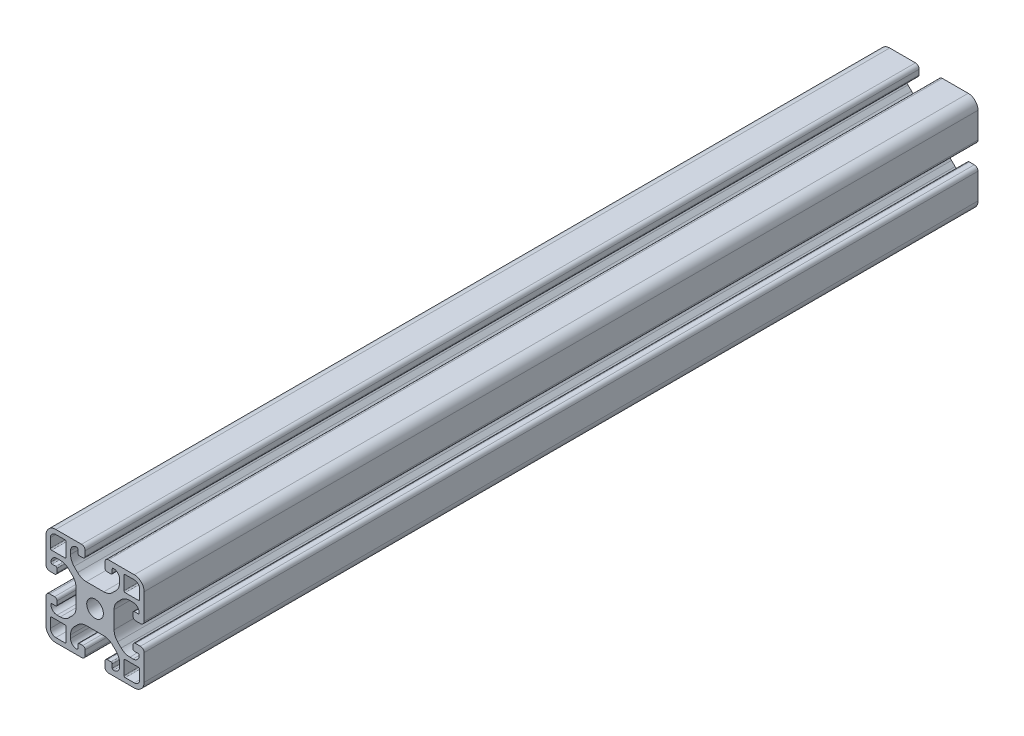
SolidWorks part; units mm, degrees
ref_plane "Plan de face" through (0, 0, 0) normal (0, 0, 1) x (1, 0, 0)
ref_plane "Plan de dessus" through (0, 0, 0) normal (0, 1, 0) x (1, 0, 0)
ref_plane "Plan de droite" through (0, 0, 0) normal (1, 0, 0) x (0, 0, -1)
ref_plane "Plan1" through (0, 0, -30) normal (0, 0, -1) x (-1, 0, 0)
sketch "Esquisse1" plane through (0, 0, -30) normal (0, 0, -1) x (-1, 0, 0)
  line L0 (-4.5, 15) -> (-4.5, 13.5)
  line L1 (-4, 13) -> (-2.5, 13)
  line L2 (-4.5, 10) -> (-5.8076, 10)
  line L3 (-9.3431, 11.4645) -> (-10.7855, 12.9069)
  line L4 (-12.25, 16.4424) -> (-12.25, 23.5576)
  line L5 (-10.7855, 27.0931) -> (-9.3431, 28.5355)
  line L6 (-5.8076, 30) -> (-4.5, 30)
  line L7 (-2.5, 27) -> (-4, 27)
  line L8 (-4.5, 26.5) -> (-4.5, 25)
  line L9 (-3.5, 24) -> (-1.5, 24)
  line L10 (0, 25.5) -> (0, 36)
  line L11 (-4, 40) -> (-14.5, 40)
  line L12 (-16, 38.5) -> (-16, 36.5)
  line L13 (-15, 35.5) -> (-13.5, 35.5)
  line L14 (-13, 36) -> (-13, 37.5)
  line L15 (-10, 35.5) -> (-10, 34.1924)
  line L16 (-11.4645, 30.6569) -> (-12.9069, 29.2145)
  line L17 (-16.4424, 27.75) -> (-23.5576, 27.75)
  line L18 (-27.0931, 29.2145) -> (-28.5355, 30.6569)
  line L19 (-30, 34.1924) -> (-30, 35.5)
  line L20 (-27, 37.5) -> (-27, 36)
  line L21 (-26.5, 35.5) -> (-25, 35.5)
  line L22 (-24, 36.5) -> (-24, 38.5)
  line L23 (-25.5, 40) -> (-36, 40)
  line L24 (-40, 36) -> (-40, 25.5)
  line L25 (-38.5, 24) -> (-36.5, 24)
  line L26 (-35.5, 25) -> (-35.5, 26.5)
  line L27 (-36, 27) -> (-37.5, 27)
  line L28 (-35.5, 30) -> (-34.1924, 30)
  line L29 (-30.6569, 28.5355) -> (-29.2145, 27.0931)
  line L30 (-27.75, 23.5576) -> (-27.75, 16.4424)
  line L31 (-29.2145, 12.9069) -> (-30.6569, 11.4645)
  line L32 (-34.1924, 10) -> (-35.5, 10)
  line L33 (-37.5, 13) -> (-36, 13)
  line L34 (-35.5, 13.5) -> (-35.5, 15)
  line L35 (-36.5, 16) -> (-38.5, 16)
  line L36 (-40, 14.5) -> (-40, 4)
  line L37 (-36, 0) -> (-25.5, 0)
  line L38 (-24, 1.5) -> (-24, 3.5)
  line L39 (-25, 4.5) -> (-26.5, 4.5)
  line L40 (-27, 4) -> (-27, 2.5)
  line L41 (-30, 4.5) -> (-30, 5.8076)
  line L42 (-28.5355, 9.3431) -> (-27.0931, 10.7855)
  line L43 (-23.5576, 12.25) -> (-16.4424, 12.25)
  line L44 (-12.9069, 10.7855) -> (-11.4645, 9.3431)
  line L45 (-10, 5.8076) -> (-10, 4.5)
  line L46 (-13, 2.5) -> (-13, 4)
  line L47 (-13.5, 4.5) -> (-15, 4.5)
  line L48 (-16, 3.5) -> (-16, 1.5)
  line L49 (-14.5, 0) -> (-4, 0)
  line L50 (0, 4) -> (0, 14.5)
  line L51 (-1.5, 16) -> (-3.5, 16)
  line L52 (-4, 1.8) -> (-7.7, 1.8)
  line L53 (-8.2, 2.3) -> (-8.2, 7.7)
  line L54 (-7.7, 8.2) -> (-2.3, 8.2)
  line L55 (-1.8, 7.7) -> (-1.8, 4)
  line L56 (-38.2, 4) -> (-38.2, 7.7)
  line L57 (-37.7, 8.2) -> (-32.3, 8.2)
  line L58 (-31.8, 7.7) -> (-31.8, 2.3)
  line L59 (-32.3, 1.8) -> (-36, 1.8)
  line L60 (-36, 38.2) -> (-32.3, 38.2)
  line L61 (-31.8, 37.7) -> (-31.8, 32.3)
  line L62 (-32.3, 31.8) -> (-37.7, 31.8)
  line L63 (-38.2, 32.3) -> (-38.2, 36)
  line L64 (-1.8, 36) -> (-1.8, 32.3)
  line L65 (-2.3, 31.8) -> (-7.7, 31.8)
  line L66 (-8.2, 32.3) -> (-8.2, 37.7)
  line L67 (-7.7, 38.2) -> (-4, 38.2)
  arc A0 (-4.5, 13.5) -> (-4, 13) centre (-4, 13.5) ccw
  arc A1 (-2.5, 13) -> (-2, 12.5) centre (-2.5, 12.5) cw
  arc A2 (-2, 12.5) -> (-4.5, 10) centre (-4.5, 12.5) cw
  arc A3 (-5.8076, 10) -> (-9.3431, 11.4645) centre (-5.8076, 15) cw
  arc A4 (-10.7855, 12.9069) -> (-12.25, 16.4424) centre (-7.25, 16.4424) cw
  arc A5 (-12.25, 23.5576) -> (-10.7855, 27.0931) centre (-7.25, 23.5576) cw
  arc A6 (-9.3431, 28.5355) -> (-5.8076, 30) centre (-5.8076, 25) cw
  arc A7 (-4.5, 30) -> (-2, 27.5) centre (-4.5, 27.5) cw
  arc A8 (-2, 27.5) -> (-2.5, 27) centre (-2.5, 27.5) cw
  arc A9 (-4, 27) -> (-4.5, 26.5) centre (-4, 26.5) ccw
  arc A10 (-4.5, 25) -> (-3.5, 24) centre (-3.5, 25) ccw
  arc A11 (-1.5, 24) -> (0, 25.5) centre (-1.5, 25.5) ccw
  arc A12 (0, 36) -> (-4, 40) centre (-4, 36) ccw
  arc A13 (-14.5, 40) -> (-16, 38.5) centre (-14.5, 38.5) ccw
  arc A14 (-16, 36.5) -> (-15, 35.5) centre (-15, 36.5) ccw
  arc A15 (-13.5, 35.5) -> (-13, 36) centre (-13.5, 36) ccw
  arc A16 (-13, 37.5) -> (-12.5, 38) centre (-12.5, 37.5) cw
  arc A17 (-12.5, 38) -> (-10, 35.5) centre (-12.5, 35.5) cw
  arc A18 (-10, 34.1924) -> (-11.4645, 30.6569) centre (-15, 34.1924) cw
  arc A19 (-12.9069, 29.2145) -> (-16.4424, 27.75) centre (-16.4424, 32.75) cw
  arc A20 (-23.5576, 27.75) -> (-27.0931, 29.2145) centre (-23.5576, 32.75) cw
  arc A21 (-28.5355, 30.6569) -> (-30, 34.1924) centre (-25, 34.1924) cw
  arc A22 (-30, 35.5) -> (-27.5, 38) centre (-27.5, 35.5) cw
  arc A23 (-27.5, 38) -> (-27, 37.5) centre (-27.5, 37.5) cw
  arc A24 (-27, 36) -> (-26.5, 35.5) centre (-26.5, 36) ccw
  arc A25 (-25, 35.5) -> (-24, 36.5) centre (-25, 36.5) ccw
  arc A26 (-24, 38.5) -> (-25.5, 40) centre (-25.5, 38.5) ccw
  arc A27 (-36, 40) -> (-40, 36) centre (-36, 36) ccw
  arc A28 (-40, 25.5) -> (-38.5, 24) centre (-38.5, 25.5) ccw
  arc A29 (-36.5, 24) -> (-35.5, 25) centre (-36.5, 25) ccw
  arc A30 (-35.5, 26.5) -> (-36, 27) centre (-36, 26.5) ccw
  arc A31 (-37.5, 27) -> (-38, 27.5) centre (-37.5, 27.5) cw
  arc A32 (-38, 27.5) -> (-35.5, 30) centre (-35.5, 27.5) cw
  arc A33 (-34.1924, 30) -> (-30.6569, 28.5355) centre (-34.1924, 25) cw
  arc A34 (-29.2145, 27.0931) -> (-27.75, 23.5576) centre (-32.75, 23.5576) cw
  arc A35 (-27.75, 16.4424) -> (-29.2145, 12.9069) centre (-32.75, 16.4424) cw
  arc A36 (-30.6569, 11.4645) -> (-34.1924, 10) centre (-34.1924, 15) cw
  arc A37 (-35.5, 10) -> (-38, 12.5) centre (-35.5, 12.5) cw
  arc A38 (-38, 12.5) -> (-37.5, 13) centre (-37.5, 12.5) cw
  arc A39 (-36, 13) -> (-35.5, 13.5) centre (-36, 13.5) ccw
  arc A40 (-35.5, 15) -> (-36.5, 16) centre (-36.5, 15) ccw
  arc A41 (-38.5, 16) -> (-40, 14.5) centre (-38.5, 14.5) ccw
  arc A42 (-40, 4) -> (-36, 0) centre (-36, 4) ccw
  arc A43 (-25.5, 0) -> (-24, 1.5) centre (-25.5, 1.5) ccw
  arc A44 (-24, 3.5) -> (-25, 4.5) centre (-25, 3.5) ccw
  arc A45 (-26.5, 4.5) -> (-27, 4) centre (-26.5, 4) ccw
  arc A46 (-27, 2.5) -> (-27.5, 2) centre (-27.5, 2.5) cw
  arc A47 (-27.5, 2) -> (-30, 4.5) centre (-27.5, 4.5) cw
  arc A48 (-30, 5.8076) -> (-28.5355, 9.3431) centre (-25, 5.8076) cw
  arc A49 (-27.0931, 10.7855) -> (-23.5576, 12.25) centre (-23.5576, 7.25) cw
  arc A50 (-16.4424, 12.25) -> (-12.9069, 10.7855) centre (-16.4424, 7.25) cw
  arc A51 (-11.4645, 9.3431) -> (-10, 5.8076) centre (-15, 5.8076) cw
  arc A52 (-10, 4.5) -> (-12.5, 2) centre (-12.5, 4.5) cw
  arc A53 (-12.5, 2) -> (-13, 2.5) centre (-12.5, 2.5) cw
  arc A54 (-13, 4) -> (-13.5, 4.5) centre (-13.5, 4) ccw
  arc A55 (-15, 4.5) -> (-16, 3.5) centre (-15, 3.5) ccw
  arc A56 (-16, 1.5) -> (-14.5, 0) centre (-14.5, 1.5) ccw
  arc A57 (-4, 0) -> (0, 4) centre (-4, 4) ccw
  arc A58 (0, 14.5) -> (-1.5, 16) centre (-1.5, 14.5) ccw
  arc A59 (-3.5, 16) -> (-4.5, 15) centre (-3.5, 15) ccw
  circle A60 centre (-20, 20) radius 3.4
  arc A61 (-1.8, 4) -> (-4, 1.8) centre (-4, 4) cw
  arc A62 (-7.7, 1.8) -> (-8.2, 2.3) centre (-7.7, 2.3) cw
  arc A63 (-8.2, 7.7) -> (-7.7, 8.2) centre (-7.7, 7.7) cw
  arc A64 (-2.3, 8.2) -> (-1.8, 7.7) centre (-2.3, 7.7) cw
  arc A65 (-36, 1.8) -> (-38.2, 4) centre (-36, 4) cw
  arc A66 (-38.2, 7.7) -> (-37.7, 8.2) centre (-37.7, 7.7) cw
  arc A67 (-32.3, 8.2) -> (-31.8, 7.7) centre (-32.3, 7.7) cw
  arc A68 (-31.8, 2.3) -> (-32.3, 1.8) centre (-32.3, 2.3) cw
  arc A69 (-38.2, 36) -> (-36, 38.2) centre (-36, 36) cw
  arc A70 (-32.3, 38.2) -> (-31.8, 37.7) centre (-32.3, 37.7) cw
  arc A71 (-31.8, 32.3) -> (-32.3, 31.8) centre (-32.3, 32.3) cw
  arc A72 (-37.7, 31.8) -> (-38.2, 32.3) centre (-37.7, 32.3) cw
  arc A73 (-4, 38.2) -> (-1.8, 36) centre (-4, 36) cw
  arc A74 (-1.8, 32.3) -> (-2.3, 31.8) centre (-2.3, 32.3) cw
  arc A75 (-7.7, 31.8) -> (-8.2, 32.3) centre (-7.7, 32.3) cw
  arc A76 (-8.2, 37.7) -> (-7.7, 38.2) centre (-7.7, 37.7) cw
extrude "Boss.-Extru.1" add sketch "Esquisse1" against normal blind 340
